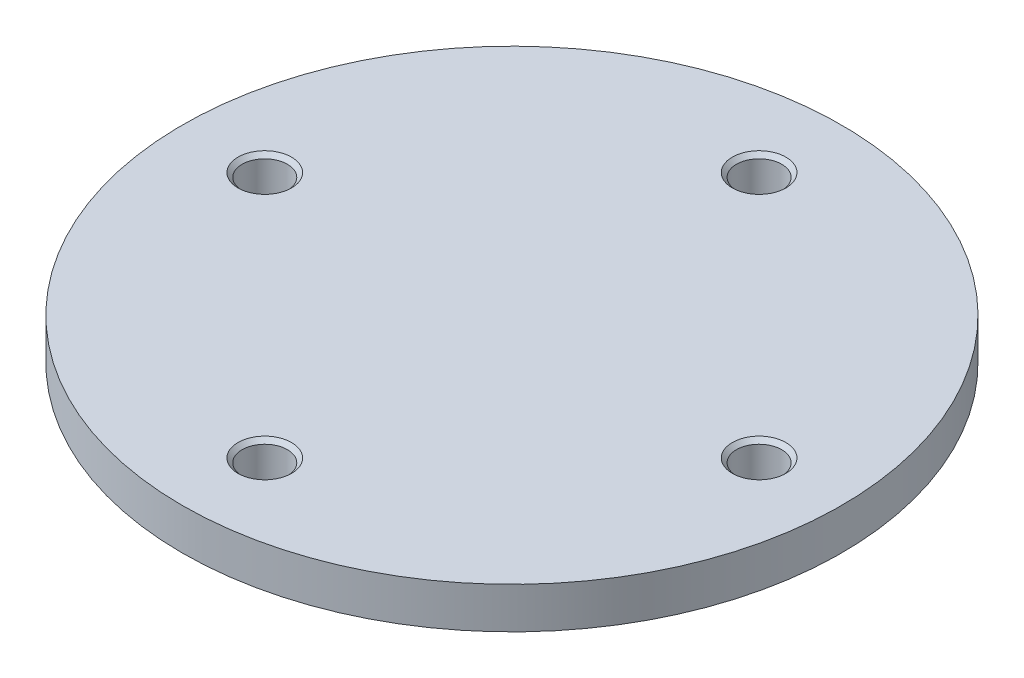
SolidWorks part; units mm, degrees
ref_plane "前视基准面" through (0, 0, 0) normal (0, 0, 1) x (1, 0, 0)
ref_plane "上视基准面" through (0, 0, 0) normal (0, 1, 0) x (1, 0, 0)
ref_plane "右视基准面" through (0, 0, 0) normal (1, 0, 0) x (0, 0, -1)
other "Configuration Table"
sketch "草图1" plane through (0, 0, 0) normal (0, 1, 0) x (1, 0, 0)
  line L0 (-1.7349, 1.8) -> (1.7349, 1.8)
  arc A0 (-1.7349, 1.8) -> (1.7349, 1.8) centre (0, 0) ccw
  circle A1 centre (0, 0) radius 10
  dimension "D1" = 5
  dimension "D2" = 20
  dimension "D3" = 1.8
extrude "凸台-拉伸1" add sketch "草图1" along normal blind 21
sketch "草图2" plane through (0, 21, 0) normal (0, 1, 0) x (1, 0, 0)
  circle A0 centre (0, 0) radius 40
  dimension "D1" = 80
extrude "凸台-拉伸2" add sketch "草图2" along normal blind 5
chamfer "倒角1" distance 10 angle 45 1 edges at (0, 21, 10)
sketch "草图3" plane through (0, 26, 0) normal (0, 1, 0) x (1, 0, 0)
  circle A0 centre (0, 0) radius 30 construction
  circle A1 centre (0, 30) radius 2.75
  circle A2 centre (30, 0) radius 2.75
  circle A3 centre (0, -30) radius 2.75
  circle A4 centre (-30, 0) radius 2.75
  point P14 (0, 0)
  dimension "D1" = 60
  dimension "D2" = 5.5
  dimension "D3" = 4
extrude "切除-拉伸2" cut sketch "草图3" against normal blind 5
chamfer "倒角2" distance 0.5 angle 45 4 edges at (0, 26, 32.75) (-30, 26, 2.75) (0, 26, -27.25) (30, 26, 2.75)
sketch "草图4" plane through (0, 0, 0) normal (0, 0, 1) x (1, 0, 0)
  line L0 (-20, 21) -> (20, 21) construction
  circle A0 centre (0, 16.5) radius 1.5
  point P4 (0, 0)
  dimension "D1" = 3
  dimension "D2" = 4.5
extrude "切除-拉伸3" cut sketch "草图4" against normal through all
